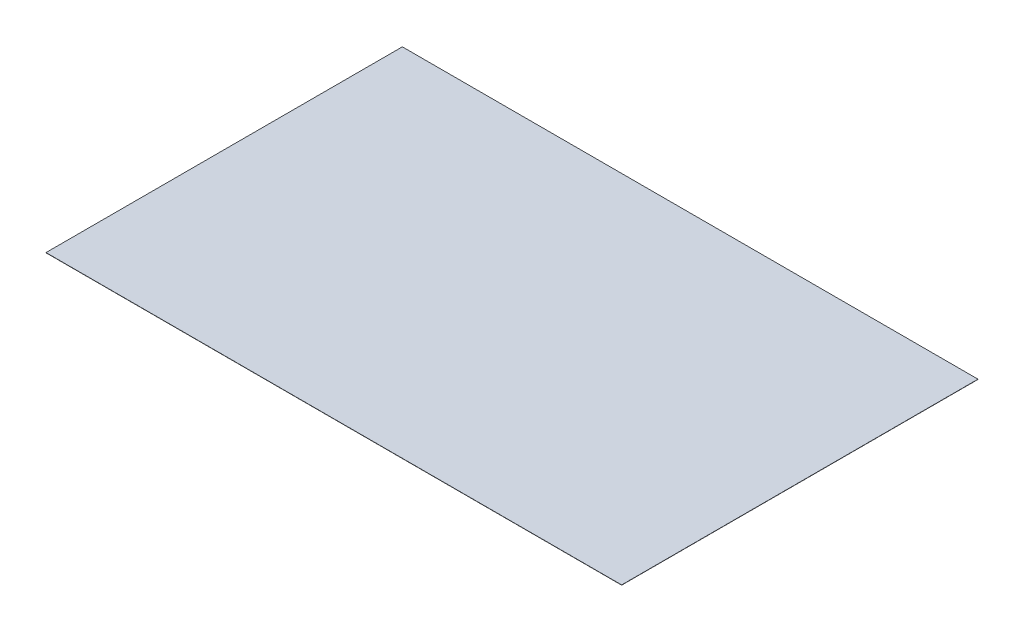
SolidWorks part; units mm, degrees
ref_plane "Front Plane" through (0, 0, 0) normal (0, 0, 1) x (1, 0, 0)
ref_plane "Top Plane" through (0, 0, 0) normal (0, 1, 0) x (1, 0, 0)
ref_plane "Right Plane" through (0, 0, 0) normal (1, 0, 0) x (0, 0, -1)
sketch "Sketch1" plane through (0, 0, 0) normal (0, 1, 0) x (1, 0, 0)
  line L1 (-64008, 39624) -> (64008, 39624)
  line L2 (-64008, 39624) -> (-64008, -39624)
  line L3 (-64008, -39624) -> (64008, -39624)
  line L4 (64008, 39624) -> (64008, -39624)
  point P4 (64008, 0)
  point P6 (0, 39624)
  dimension "D1" = 79248
  dimension "D2" = 128016
extrude "Boss-Extrude1" add sketch "Sketch1" along normal blind 50.8 contours L3 L4 L1 L2
